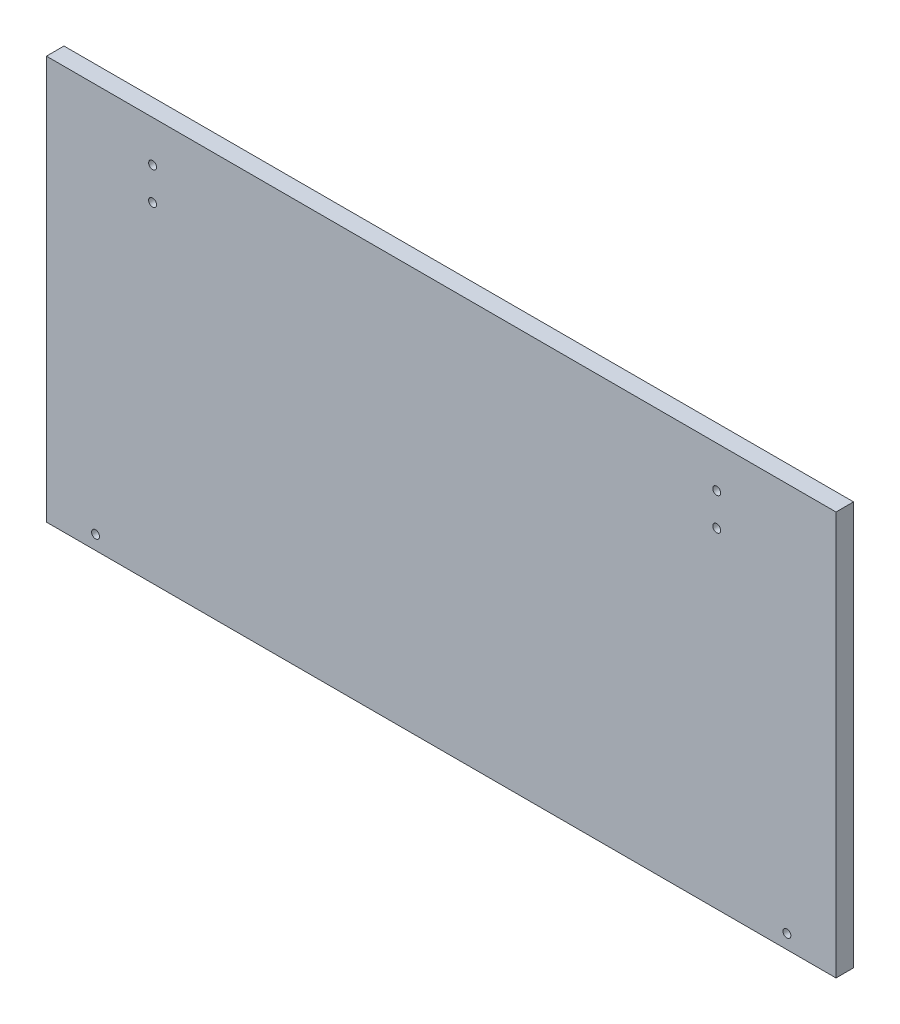
SolidWorks part; units mm, degrees
material "Multistrato di pioppo"
ref_plane "Piano frontale" through (0, 0, 0) normal (0, 0, 1) x (1, 0, 0)
ref_plane "Piano superiore" through (0, 0, 0) normal (0, 1, 0) x (1, 0, 0)
ref_plane "Piano destro" through (0, 0, 0) normal (1, 0, 0) x (0, 0, -1)
sketch "Schizzo1" plane through (0, 0, 0) normal (0, 0, 1) x (1, 0, 0)
  line L5 (-225, 115) -> (225, 115)
  line L6 (-225, 115) -> (-225, -115)
  line L7 (-225, -115) -> (225, -115)
  line L8 (225, 115) -> (225, -115)
  line L9 (-225, 115) -> (225, -115) construction
  line L10 (-225, -115) -> (225, 115) construction
  point P8 (0, 0)
  dimension "D1" = 230
  dimension "D2" = 450
extrude "Estrusione-Estrusione1" add sketch "Schizzo1" along normal blind 10
sketch "Schizzo2" plane through (0, 0, 0) normal (0, 0, -1) x (-1, 0, 0)
  circle A0 centre (-157, 91.5) radius 2.25
  circle A1 centre (-157, 73) radius 2.25
  circle A2 centre (164.5, 91.5) radius 2.25
  circle A3 centre (164.5, 73) radius 2.25
  dimension "D1" = 4.5
extrude "Taglio-Estrusione1" cut sketch "Schizzo2" against normal blind 10
sketch "Schizzo3" plane through (0, 0, 0) normal (0, 0, -1) x (-1, 0, 0)
  line L0 (197, -107) -> (-197, -107) construction
  line L1 (225, -115) -> (-225, -115) construction
  line L2 (225, 115) -> (225, -115) construction
  line L3 (-225, -115) -> (-225, 115) construction
  circle A0 centre (197, -107) radius 2.25
  circle A1 centre (-197, -107) radius 2.25
  dimension "D1" = 4.5
  dimension "D2" = 8
  dimension "D3" = 28
  dimension "D4" = 28
extrude "Taglio-Estrusione2" cut sketch "Schizzo3" against normal blind 10
